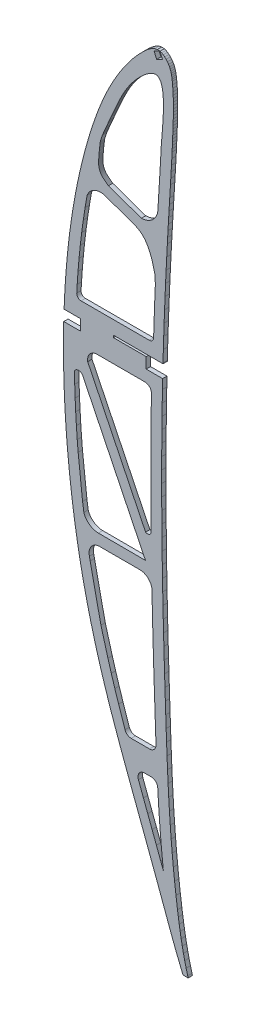
SolidWorks part; units mm, degrees
ref_plane "前视基准面" through (0, 0, 0) normal (0, 0, 1) x (1, 0, 0)
ref_plane "上视基准面" through (0, 0, 0) normal (0, 1, 0) x (1, 0, 0)
ref_plane "右视基准面" through (0, 0, 0) normal (1, 0, 0) x (0, 0, -1)
sketch "Model" plane through (0, 0, 0) normal (0, 0, 1) x (1, 0, 0)
  line L0 (80.8853, 6.7869) -> (80.6013, 7.44)
  line L1 (80.6013, 7.44) -> (79.4974, 10.0954)
  line L2 (79.4974, 10.0954) -> (78.4161, 12.7608)
  line L3 (78.4161, 12.7608) -> (77.3763, 15.3929)
  line L4 (77.3763, 15.3929) -> (76.3591, 18.0341)
  line L5 (76.3591, 18.0341) -> (75.3607, 20.682)
  line L6 (75.3607, 20.682) -> (74.3741, 23.3345)
  line L7 (74.3741, 23.3345) -> (73.3972, 25.9914)
  line L8 (73.3972, 25.9914) -> (71.4514, 31.3096)
  line L9 (71.4514, 31.3096) -> (69.4948, 36.6223)
  line L10 (69.4948, 36.6223) -> (67.5256, 41.9265)
  line L11 (67.5256, 41.9265) -> (65.5445, 47.2261)
  line L12 (65.5445, 47.2261) -> (63.5566, 52.5225)
  line L13 (63.5566, 52.5225) -> (61.5637, 57.8176)
  line L14 (61.5637, 57.8176) -> (59.5689, 63.1126)
  line L15 (59.5689, 63.1126) -> (57.5739, 68.4106)
  line L16 (57.5739, 68.4106) -> (55.595, 73.6833)
  line L17 (55.595, 73.6833) -> (53.6309, 78.9607)
  line L18 (53.6309, 78.9607) -> (51.6916, 84.2451)
  line L19 (51.6916, 84.2451) -> (49.7867, 89.5421)
  line L20 (49.7867, 89.5421) -> (47.9262, 94.854)
  line L21 (47.9262, 94.854) -> (46.1219, 100.1863)
  line L22 (46.1219, 100.1863) -> (44.3817, 105.5415)
  line L23 (44.3817, 105.5415) -> (42.7516, 110.8044)
  line L24 (42.7516, 110.8044) -> (41.1946, 116.0895)
  line L25 (41.1946, 116.0895) -> (39.7137, 121.395)
  line L26 (39.7137, 121.395) -> (38.308, 126.7217)
  line L27 (38.308, 126.7217) -> (36.9806, 132.0679)
  line L28 (36.9806, 132.0679) -> (35.7313, 137.4345)
  line L29 (35.7313, 137.4345) -> (34.5623, 142.8197)
  line L30 (34.5623, 142.8197) -> (33.4905, 148.133)
  line L31 (33.4905, 148.133) -> (32.4952, 153.4596)
  line L32 (32.4952, 153.4596) -> (31.5745, 158.7986)
  line L33 (31.5745, 158.7986) -> (30.7252, 164.1496)
  line L34 (30.7252, 164.1496) -> (29.9466, 169.5108)
  line L35 (29.9466, 169.5108) -> (29.2346, 174.8838)
  line L36 (29.2346, 174.8838) -> (28.5882, 180.2657)
  line L37 (28.5882, 180.2657) -> (28.0091, 185.6216)
  line L38 (28.0091, 185.6216) -> (27.4917, 190.9831)
  line L39 (27.4917, 190.9831) -> (27.0392, 196.3485)
  line L40 (27.0392, 196.3485) -> (26.6507, 201.7176)
  line L41 (26.6507, 201.7176) -> (26.3269, 207.0926)
  line L42 (26.3269, 207.0926) -> (26.069, 212.4715)
  line L43 (26.069, 212.4715) -> (25.8771, 217.8543)
  line L44 (25.8771, 217.8543) -> (25.7527, 223.247)
  line L45 (25.7527, 223.247) -> (25.6964, 228.6396)
  line L46 (25.6964, 228.6396) -> (25.7103, 234.0314)
  line L47 (25.7103, 234.0314) -> (25.8108, 240.4108)
  line L48 (25.979, 245.4108) -> (26.1854, 250.2005)
  line L49 (26.1854, 250.2005) -> (26.4937, 255.5881)
  line L50 (26.4937, 255.5881) -> (26.8835, 261.0353)
  line L51 (26.8835, 261.0353) -> (27.3567, 266.4741)
  line L52 (27.3567, 266.4741) -> (27.9154, 271.9036)
  line L53 (27.9154, 271.9036) -> (28.5647, 277.3221)
  line L54 (28.5647, 277.3221) -> (29.3075, 282.7286)
  line L55 (29.3075, 282.7286) -> (30.1482, 288.1194)
  line L56 (30.1482, 288.1194) -> (31.0916, 293.4957)
  line L57 (31.0916, 293.4957) -> (31.6136, 296.2351)
  line L58 (31.6136, 296.2351) -> (32.1639, 298.9677)
  line L59 (32.1639, 298.9677) -> (32.7416, 301.6935)
  line L60 (32.7416, 301.6935) -> (33.3475, 304.4135)
  line L61 (33.3475, 304.4135) -> (33.9827, 307.1278)
  line L62 (33.9827, 307.1278) -> (34.6473, 309.8343)
  line L63 (34.6473, 309.8343) -> (35.3421, 312.5352)
  line L64 (35.3421, 312.5352) -> (36.0863, 315.2993)
  line L65 (36.0863, 315.2993) -> (36.8648, 318.0549)
  line L66 (36.8648, 318.0549) -> (37.6779, 320.799)
  line L67 (37.6779, 320.799) -> (38.5296, 323.5307)
  line L68 (38.5296, 323.5307) -> (39.4217, 326.2512)
  line L69 (39.4217, 326.2512) -> (40.3556, 328.9575)
  line L70 (40.3556, 328.9575) -> (41.3351, 331.6498)
  line L71 (41.3351, 331.6498) -> (41.8619, 333.0401)
  line L72 (41.8619, 333.0401) -> (42.401, 334.426)
  line L73 (42.401, 334.426) -> (42.9544, 335.8054)
  line L74 (42.9544, 335.8054) -> (43.522, 337.1785)
  line L75 (43.522, 337.1785) -> (44.105, 338.5432)
  line L76 (44.105, 338.5432) -> (44.7043, 339.9016)
  line L77 (44.7043, 339.9016) -> (45.3191, 341.2507)
  line L78 (45.3191, 341.2507) -> (45.9834, 342.6561)
  line L79 (45.9834, 342.6561) -> (46.6672, 344.0522)
  line L80 (46.6672, 344.0522) -> (47.3714, 345.4383)
  line L81 (47.3714, 345.4383) -> (48.097, 346.8152)
  line L82 (48.097, 346.8152) -> (48.843, 348.1841)
  line L83 (48.843, 348.1841) -> (49.6134, 349.545)
  line L84 (49.6134, 349.545) -> (50.4061, 350.8988)
  line L85 (50.4061, 350.8988) -> (51.2905, 352.3538)
  line L86 (51.2905, 352.3538) -> (52.2005, 353.7948)
  line L87 (52.2005, 353.7948) -> (53.1343, 355.2179)
  line L88 (53.1343, 355.2179) -> (54.0902, 356.616)
  line L89 (54.0902, 356.616) -> (55.0674, 357.9859)
  line L90 (55.0674, 357.9859) -> (56.0621, 359.3215)
  line L91 (56.0621, 359.3215) -> (57.0745, 360.6169)
  line L92 (57.0745, 360.6169) -> (57.7043, 361.3932)
  line L93 (57.7043, 361.3932) -> (58.3456, 362.1569)
  line L94 (58.3456, 362.1569) -> (59.0031, 362.9163)
  line L95 (59.0031, 362.9163) -> (59.6826, 363.6756)
  line L96 (59.6826, 363.6756) -> (60.3889, 364.4412)
  line L97 (60.3889, 364.4412) -> (61.1287, 365.2182)
  line L98 (61.1287, 365.2182) -> (61.9058, 366.0128)
  line L99 (61.9058, 366.0128) -> (62.9912, 367.0802)
  line L100 (62.9912, 367.0802) -> (64.1359, 368.1221)
  line L101 (64.1359, 368.1221) -> (65.3256, 369.0719)
  line L102 (65.3256, 369.0719) -> (66.5452, 369.8629)
  line L103 (66.5452, 369.8629) -> (67.7798, 370.4282)
  line L104 (67.7798, 370.4282) -> (69.015, 370.7024)
  line L105 (69.015, 370.7024) -> (70.2338, 370.6185)
  line L106 (70.2338, 370.6185) -> (70.9807, 370.3608)
  line L107 (70.9807, 370.3608) -> (71.705, 369.959)
  line L108 (71.705, 369.959) -> (72.3954, 369.4366)
  line L109 (72.3954, 369.4366) -> (73.0402, 368.8132)
  line L110 (73.0402, 368.8132) -> (73.6293, 368.1132)
  line L111 (73.6293, 368.1132) -> (74.1518, 367.3563)
  line L112 (74.1518, 367.3563) -> (74.5967, 366.5669)
  line L113 (74.5967, 366.5669) -> (74.9201, 365.8533)
  line L114 (74.9201, 365.8533) -> (75.1829, 365.1311)
  line L115 (75.1829, 365.1311) -> (75.3928, 364.4026)
  line L116 (75.3928, 364.4026) -> (75.559, 363.6681)
  line L117 (75.559, 363.6681) -> (75.6914, 362.9282)
  line L118 (75.6914, 362.9282) -> (75.7979, 362.1851)
  line L119 (75.7979, 362.1851) -> (75.8876, 361.4383)
  line L120 (75.8876, 361.4383) -> (76.0269, 360.1051)
  line L121 (76.0269, 360.1051) -> (76.1424, 358.7659)
  line L122 (76.1424, 358.7659) -> (76.2351, 357.4237)
  line L123 (76.2351, 357.4237) -> (76.3068, 356.0785)
  line L124 (76.3068, 356.0785) -> (76.3596, 354.7315)
  line L125 (76.3596, 354.7315) -> (76.3945, 353.3828)
  line L126 (76.3945, 353.3828) -> (76.4123, 352.0343)
  line L127 (76.4123, 352.0343) -> (76.4142, 350.6851)
  line L128 (76.4142, 350.6851) -> (76.403, 349.3353)
  line L129 (76.403, 349.3353) -> (76.3798, 347.988)
  line L130 (76.3798, 347.988) -> (76.3465, 346.6403)
  line L131 (76.3465, 346.6403) -> (76.3062, 345.2932)
  line L132 (76.3062, 345.2932) -> (76.2599, 343.9469)
  line L133 (76.2599, 343.9469) -> (76.2107, 342.5995)
  line L134 (76.2107, 342.5995) -> (76.1585, 341.2499)
  line L135 (76.1585, 341.2499) -> (76.1053, 339.9003)
  line L136 (76.1053, 339.9003) -> (76.0491, 338.5516)
  line L137 (76.0491, 338.5516) -> (75.9918, 337.2028)
  line L138 (75.9918, 337.2028) -> (75.9317, 335.8529)
  line L139 (75.9317, 335.8529) -> (75.8695, 334.5039)
  line L140 (75.8695, 334.5039) -> (75.8052, 333.1548)
  line L141 (75.8052, 333.1548) -> (75.668, 330.4533)
  line L142 (75.668, 330.4533) -> (75.5216, 327.7523)
  line L143 (75.5216, 327.7523) -> (75.3683, 325.0521)
  line L144 (75.3683, 325.0521) -> (75.2089, 322.3525)
  line L145 (75.2089, 322.3525) -> (75.0464, 319.6539)
  line L146 (75.0464, 319.6539) -> (74.7156, 314.2543)
  line L147 (74.7156, 314.2543) -> (74.5523, 311.5536)
  line L148 (74.5523, 311.5536) -> (74.3899, 308.853)
  line L149 (74.3899, 308.853) -> (74.2295, 306.1534)
  line L150 (74.2295, 306.1534) -> (74.0721, 303.454)
  line L151 (74.0721, 303.454) -> (73.9167, 300.7546)
  line L152 (73.9167, 300.7546) -> (73.7644, 298.0534)
  line L153 (73.7644, 298.0534) -> (73.6161, 295.3524)
  line L154 (73.6161, 295.3524) -> (73.3292, 289.9557)
  line L155 (73.3292, 289.9557) -> (73.0573, 284.5597)
  line L156 (73.0573, 284.5597) -> (72.8014, 279.1644)
  line L157 (72.8014, 279.1644) -> (72.5605, 273.7688)
  line L158 (72.5605, 273.7688) -> (72.3357, 268.3718)
  line L159 (72.3357, 268.3718) -> (72.128, 262.9726)
  line L160 (72.128, 262.9726) -> (71.9384, 257.5722)
  line L161 (71.9384, 257.5722) -> (71.7655, 252.1795)
  line L162 (71.7655, 252.1795) -> (71.6105, 246.7887)
  line L163 (71.6105, 246.7887) -> (71.6009, 246.4108)
  line L164 (71.4292, 240.4108) -> (71.3535, 236.0072)
  line L165 (71.3535, 236.0072) -> (71.2516, 230.6156)
  line L166 (71.2516, 230.6156) -> (71.1668, 225.2228)
  line L167 (71.1668, 225.2228) -> (71.1, 219.8287)
  line L168 (71.1, 219.8287) -> (71.05, 214.4404)
  line L169 (71.05, 214.4404) -> (71.0169, 209.0538)
  line L170 (71.0169, 209.0538) -> (70.9998, 203.668)
  line L171 (70.9998, 203.668) -> (70.9987, 198.2818)
  line L172 (70.9987, 198.2818) -> (71.0127, 192.8963)
  line L173 (71.0127, 192.8963) -> (71.0407, 187.5094)
  line L174 (71.0407, 187.5094) -> (71.0817, 182.121)
  line L175 (71.0817, 182.121) -> (71.1367, 176.7363)
  line L176 (71.1367, 176.7363) -> (71.2046, 171.3532)
  line L177 (71.2046, 171.3532) -> (71.2844, 165.9705)
  line L178 (71.2844, 165.9705) -> (71.3772, 160.5894)
  line L179 (71.3772, 160.5894) -> (71.4821, 155.2079)
  line L180 (71.4821, 155.2079) -> (71.5979, 149.8258)
  line L181 (71.5979, 149.8258) -> (71.7269, 144.4423)
  line L182 (71.7269, 144.4423) -> (71.8658, 139.0603)
  line L183 (71.8658, 139.0603) -> (72.0156, 133.6807)
  line L184 (72.0156, 133.6807) -> (72.1743, 128.3025)
  line L185 (72.1743, 128.3025) -> (72.3411, 122.9246)
  line L186 (72.3411, 122.9246) -> (72.5138, 117.546)
  line L187 (72.5138, 117.546) -> (72.6926, 112.1667)
  line L188 (72.6926, 112.1667) -> (72.8755, 106.7856)
  line L189 (72.8755, 106.7856) -> (73.0624, 101.4046)
  line L190 (73.0624, 101.4046) -> (73.2582, 96.026)
  line L191 (73.2582, 96.026) -> (73.468, 90.6491)
  line L192 (73.468, 90.6491) -> (73.6997, 85.2731)
  line L193 (73.6997, 85.2731) -> (73.9573, 79.8992)
  line L194 (73.9573, 79.8992) -> (74.248, 74.5257)
  line L195 (74.248, 74.5257) -> (74.5777, 69.153)
  line L196 (74.5777, 69.153) -> (74.9516, 63.7752)
  line L197 (74.9516, 63.7752) -> (75.3734, 58.4025)
  line L198 (75.3734, 58.4025) -> (75.845, 53.0339)
  line L199 (75.845, 53.0339) -> (76.3714, 47.6708)
  line L200 (76.3714, 47.6708) -> (76.9547, 42.3122)
  line L201 (76.9547, 42.3122) -> (77.5979, 36.9581)
  line L202 (77.5979, 36.9581) -> (78.3039, 31.6088)
  line L203 (78.3039, 31.6088) -> (78.6857, 28.9169)
  line L204 (78.6857, 28.9169) -> (79.0902, 26.23)
  line L205 (79.0902, 26.23) -> (79.5207, 23.5472)
  line L206 (79.5207, 23.5472) -> (79.9848, 20.8729)
  line L207 (79.9848, 20.8729) -> (80.4876, 18.2053)
  line L208 (80.4876, 18.2053) -> (81.034, 15.5476)
  line L209 (81.034, 15.5476) -> (81.6301, 12.9011)
  line L210 (81.6301, 12.9011) -> (82.2909, 10.2144)
  line L211 (82.2909, 10.2144) -> (83.0012, 7.5408)
  line L212 (83.0012, 7.5408) -> (83.2283, 6.7869)
  line L213 (83.2283, 6.7869) -> (80.8853, 6.7869)
  line L214 (70.8079, 333.1553) -> (70.668, 330.4533)
  line L215 (70.668, 330.4533) -> (70.5216, 327.7523)
  line L216 (70.5216, 327.7523) -> (70.3683, 325.0521)
  line L217 (70.3683, 325.0521) -> (70.2089, 322.3525)
  line L218 (70.2089, 322.3525) -> (70.0464, 319.6539)
  line L219 (70.0464, 319.6539) -> (69.7156, 314.2543)
  line L220 (69.7156, 314.2543) -> (69.5523, 311.5536)
  line L221 (69.5523, 311.5536) -> (69.3899, 308.853)
  line L222 (69.3899, 308.853) -> (69.2295, 306.1534)
  line L223 (67.8279, 280.4453) -> (68.0825, 276.5082)
  line L224 (68.0825, 276.5082) -> (67.8577, 271.1112)
  line L225 (67.8577, 271.1112) -> (67.6501, 265.712)
  line L226 (67.6501, 265.712) -> (67.4604, 260.3116)
  line L227 (67.4604, 260.3116) -> (67.2875, 254.9189)
  line L228 (67.2875, 254.9189) -> (67.2781, 254.5927)
  line L229 (65.2789, 252.6501) -> (33.8086, 252.6501)
  line L230 (31.8118, 254.7644) -> (32.0157, 258.3274)
  line L231 (32.0157, 258.3274) -> (32.4055, 263.7746)
  line L232 (32.4055, 263.7746) -> (32.8787, 269.2134)
  line L233 (32.8787, 269.2134) -> (33.4374, 274.643)
  line L234 (33.4374, 274.643) -> (34.0867, 280.0615)
  line L235 (34.0867, 280.0615) -> (34.8296, 285.468)
  line L236 (34.8296, 285.468) -> (35.6702, 290.8588)
  line L237 (35.6702, 290.8588) -> (36.6136, 296.2351)
  line L238 (25.979, 245.4108) -> (32.5375, 245.4108)
  line L239 (46.4379, 304.9504) -> (61.6579, 299.5863)
  line L240 (45.1073, 300.1185) -> (55.8979, 296.3173)
  line L241 (48.7755, 245.4108) -> (48.7755, 246.4108)
  line L242 (48.7755, 246.4108) -> (71.6009, 246.4108)
  line L243 (48.7755, 245.4108) -> (63.8719, 245.4108)
  line L244 (70.1941, 370.5895) -> (67.4692, 369.3364)
  line L245 (67.4692, 369.3364) -> (68.7212, 366.6114)
  line L246 (68.7212, 366.6114) -> (71.4472, 367.8635)
  line L247 (71.4472, 367.8635) -> (70.1941, 370.5895)
  line L248 (63.8719, 240.4108) -> (63.8719, 245.4108)
  line L249 (33.5375, 240.4108) -> (33.5375, 245.4108)
  line L250 (33.5375, 245.4108) -> (32.5375, 245.4108)
  line L251 (69.1796, 75.7899) -> (69.248, 74.5257)
  line L252 (69.248, 74.5257) -> (69.5777, 69.153)
  line L253 (69.5777, 69.153) -> (69.9516, 63.7752)
  line L254 (69.9516, 63.7752) -> (70.3734, 58.4025)
  line L255 (70.3734, 58.4025) -> (70.845, 53.0339)
  line L256 (70.845, 53.0339) -> (71.7794, 43.9225)
  line L257 (71.7794, 43.9225) -> (70.5445, 47.2261)
  line L258 (70.5445, 47.2261) -> (68.5566, 52.5225)
  line L259 (68.5566, 52.5225) -> (66.5637, 57.8176)
  line L260 (66.5637, 57.8176) -> (64.5689, 63.1126)
  line L261 (64.5689, 63.1126) -> (62.5739, 68.4106)
  line L262 (62.5739, 68.4106) -> (60.2608, 74.5737)
  line L263 (63.0695, 78.6278) -> (66.184, 78.6278)
  line L264 (34.5052, 172.8415) -> (35.096, 168.7702)
  line L265 (66.1092, 179.4287) -> (66.1402, 176.5617)
  line L266 (41.8041, 163.8587) -> (63.5371, 163.7929)
  line L267 (66.4821, 154.2874) -> (66.5979, 149.8258)
  line L268 (66.5979, 149.8258) -> (66.7269, 144.4423)
  line L269 (66.7269, 144.4423) -> (66.8658, 139.0603)
  line L270 (66.8658, 139.0603) -> (67.0156, 133.6807)
  line L271 (67.0156, 133.6807) -> (67.3276, 123.1102)
  line L272 (32.4506, 191.4706) -> (32.0392, 196.3485)
  line L273 (32.0392, 196.3485) -> (31.6507, 201.7176)
  line L274 (31.6507, 201.7176) -> (31.3269, 207.0926)
  line L275 (31.3269, 207.0926) -> (31.069, 212.4715)
  line L276 (31.069, 212.4715) -> (30.8771, 217.8543)
  line L277 (30.8771, 217.8543) -> (30.7527, 223.247)
  line L278 (41.1836, 234.9868) -> (63.2728, 234.9868)
  line L279 (66.2724, 231.9396) -> (66.1668, 225.2228)
  line L280 (66.1668, 225.2228) -> (66.1, 219.8287)
  line L281 (65.9993, 201.1058) -> (65.9987, 198.2818)
  line L282 (65.9987, 198.2818) -> (66.0127, 192.8963)
  line L283 (66.0127, 192.8963) -> (66.0407, 187.5094)
  line L284 (66.0407, 187.5094) -> (66.0817, 182.121)
  line L285 (66.0817, 182.121) -> (66.1092, 179.4287)
  line L286 (37.9929, 150.7963) -> (37.654, 152.5392)
  line L287 (68.2243, 96.9576) -> (68.3862, 92.5107)
  line L288 (65.3882, 89.4015) -> (56.9232, 89.4015)
  line L289 (54.0814, 91.44) -> (51.1219, 100.1863)
  line L290 (51.1219, 100.1863) -> (49.3817, 105.5415)
  line L291 (49.3817, 105.5415) -> (47.7516, 110.8044)
  line L292 (47.7516, 110.8044) -> (46.1946, 116.0895)
  line L293 (46.1946, 116.0895) -> (42.9636, 127.6653)
  line L294 (33.5375, 240.4108) -> (25.8108, 240.4108)
  line L295 (63.8719, 240.4108) -> (71.4292, 240.4108)
  line L296 (32.4506, 191.4706) -> (34.5052, 172.8415)
  line L297 (42.9636, 127.6653) -> (37.9929, 150.7963)
  line L298 (68.2243, 96.9576) -> (67.3276, 123.1102)
  line L299 (65.9993, 201.1058) -> (66.1, 219.8287)
  line L300 (63.5763, 175.1182) -> (36.8687, 229.8768)
  line L301 (63.5371, 163.7929) -> (34.6638, 222.9921)
  line L302 (61.2175, 158.7878) -> (43.0281, 158.7878)
  line L303 (42.6779, 320.7993) -> (43.6579, 323.8303)
  line L304 (43.6579, 323.8303) -> (43.7879, 324.1303)
  line L305 (43.7879, 324.1303) -> (43.9179, 324.4303)
  line L306 (43.9179, 324.4303) -> (44.0379, 324.7293)
  line L307 (44.0379, 324.7293) -> (44.1679, 325.0293)
  line L308 (44.1679, 325.0293) -> (44.2979, 325.3293)
  line L309 (44.2979, 325.3293) -> (44.4279, 325.6283)
  line L310 (44.4279, 325.6283) -> (44.5579, 325.9283)
  line L311 (44.5579, 325.9283) -> (44.6879, 326.2273)
  line L312 (44.6879, 326.2273) -> (44.8079, 326.5263)
  line L313 (44.8079, 326.5263) -> (44.9379, 326.8263)
  line L314 (44.9379, 326.8263) -> (45.0679, 327.1253)
  line L315 (45.0679, 327.1253) -> (45.1979, 327.4243)
  line L316 (45.1979, 327.4243) -> (45.3279, 327.7223)
  line L317 (45.3279, 327.7223) -> (45.4579, 328.0213)
  line L318 (45.4579, 328.0213) -> (45.5779, 328.3203)
  line L319 (45.5779, 328.3203) -> (45.7079, 328.6183)
  line L320 (45.7079, 328.6183) -> (45.8379, 328.9163)
  line L321 (45.8379, 328.9163) -> (45.9679, 329.2143)
  line L322 (45.9679, 329.2143) -> (46.0979, 329.5123)
  line L323 (46.0979, 329.5123) -> (46.2279, 329.8093)
  line L324 (46.2279, 329.8093) -> (46.3479, 330.1063)
  line L325 (46.3479, 330.1063) -> (46.4779, 330.4043)
  line L326 (46.4779, 330.4043) -> (46.6079, 330.7003)
  line L327 (46.6079, 330.7003) -> (46.7379, 330.9973)
  line L328 (46.7379, 330.9973) -> (46.8679, 331.2933)
  line L329 (46.8679, 331.2933) -> (46.9879, 331.5893)
  line L330 (46.9879, 331.5893) -> (47.1179, 331.8853)
  line L331 (47.1179, 331.8853) -> (47.2479, 332.1803)
  line L332 (47.2479, 332.1803) -> (47.3779, 332.4753)
  line L333 (47.3779, 332.4753) -> (47.5079, 332.7703)
  line L334 (47.5079, 332.7703) -> (47.6379, 333.0653)
  line L335 (47.6379, 333.0653) -> (47.7679, 333.3593)
  line L336 (47.7679, 333.3593) -> (47.8879, 333.6533)
  line L337 (47.8879, 333.6533) -> (48.0179, 333.9463)
  line L338 (48.0179, 333.9463) -> (48.1479, 334.2393)
  line L339 (48.1479, 334.2393) -> (48.2779, 334.5323)
  line L340 (48.2779, 334.5323) -> (48.4079, 334.8243)
  line L341 (48.4079, 334.8243) -> (48.5379, 335.1163)
  line L342 (48.5379, 335.1163) -> (48.6579, 335.4073)
  line L343 (48.6579, 335.4073) -> (48.7879, 335.6983)
  line L344 (48.7879, 335.6983) -> (48.9179, 335.9893)
  line L345 (48.9179, 335.9893) -> (49.0479, 336.2793)
  line L346 (49.0479, 336.2793) -> (49.1779, 336.5693)
  line L347 (49.1779, 336.5693) -> (49.3079, 336.8583)
  line L348 (49.3079, 336.8583) -> (49.4379, 337.1463)
  line L349 (49.4379, 337.1463) -> (49.5579, 337.4353)
  line L350 (49.5579, 337.4353) -> (49.6879, 337.7223)
  line L351 (49.6879, 337.7223) -> (49.8179, 338.0093)
  line L352 (49.8179, 338.0093) -> (49.9479, 338.2963)
  line L353 (49.9479, 338.2963) -> (50.0779, 338.5823)
  line L354 (50.0779, 338.5823) -> (50.2079, 338.8683)
  line L355 (50.2079, 338.8683) -> (50.3379, 339.1533)
  line L356 (50.3379, 339.1533) -> (50.4579, 339.4373)
  line L357 (50.4579, 339.4373) -> (50.5879, 339.7213)
  line L358 (50.5879, 339.7213) -> (50.7179, 340.0053)
  line L359 (50.7179, 340.0053) -> (50.8479, 340.2883)
  line L360 (50.8479, 340.2883) -> (50.9779, 340.5703)
  line L361 (50.9779, 340.5703) -> (51.1079, 340.8523)
  line L362 (51.1079, 340.8523) -> (51.2379, 341.1343)
  line L363 (51.2379, 341.1343) -> (51.3779, 341.4153)
  line L364 (51.3779, 341.4153) -> (51.5079, 341.6963)
  line L365 (51.5079, 341.6963) -> (51.6379, 341.9763)
  line L366 (51.6379, 341.9763) -> (51.7779, 342.2553)
  line L367 (51.7779, 342.2553) -> (51.9079, 342.5353)
  line L368 (51.9079, 342.5353) -> (52.0479, 342.8143)
  line L369 (52.0479, 342.8143) -> (52.1779, 343.0923)
  line L370 (52.1779, 343.0923) -> (52.3179, 343.3703)
  line L371 (52.3179, 343.3703) -> (52.4579, 343.6483)
  line L372 (52.4579, 343.6483) -> (52.5979, 343.9253)
  line L373 (52.5979, 343.9253) -> (52.7479, 344.2023)
  line L374 (52.7479, 344.2023) -> (52.8879, 344.4793)
  line L375 (52.8879, 344.4793) -> (53.0379, 344.7553)
  line L376 (53.0379, 344.7553) -> (53.1779, 345.0313)
  line L377 (53.1779, 345.0313) -> (53.3279, 345.3073)
  line L378 (53.3279, 345.3073) -> (53.4779, 345.5823)
  line L379 (53.4779, 345.5823) -> (53.6279, 345.8573)
  line L380 (53.6279, 345.8573) -> (53.7879, 346.1323)
  line L381 (53.7879, 346.1323) -> (53.9379, 346.4063)
  line L382 (53.9379, 346.4063) -> (54.0979, 346.6803)
  line L383 (54.0979, 346.6803) -> (54.2579, 346.9543)
  line L384 (54.2579, 346.9543) -> (54.4179, 347.2283)
  line L385 (54.4179, 347.2283) -> (54.5879, 347.5013)
  line L386 (54.5879, 347.5013) -> (54.7579, 347.7743)
  line L387 (54.7579, 347.7743) -> (54.9279, 348.0473)
  line L388 (54.9279, 348.0473) -> (55.0979, 348.3203)
  line L389 (55.0979, 348.3203) -> (55.2679, 348.5923)
  line L390 (55.2679, 348.5923) -> (55.4479, 348.8653)
  line L391 (55.4479, 348.8653) -> (55.6279, 349.1373)
  line L392 (55.6279, 349.1373) -> (55.8079, 349.4093)
  line L393 (55.8079, 349.4093) -> (55.9979, 349.6803)
  line L394 (55.9979, 349.6803) -> (56.1779, 349.9523)
  line L395 (56.1779, 349.9523) -> (56.3779, 350.2233)
  line L396 (56.3779, 350.2233) -> (56.5679, 350.4953)
  line L397 (56.5679, 350.4953) -> (56.7679, 350.7663)
  line L398 (56.7679, 350.7663) -> (56.9679, 351.0373)
  line L399 (56.9679, 351.0373) -> (57.1679, 351.3083)
  line L400 (57.1679, 351.3083) -> (57.3779, 351.5793)
  line L401 (57.3779, 351.5793) -> (57.5879, 351.8503)
  line L402 (57.5879, 351.8503) -> (57.8079, 352.1203)
  line L403 (57.8079, 352.1203) -> (58.0179, 352.3913)
  line L404 (58.0179, 352.3913) -> (58.2379, 352.6613)
  line L405 (58.2379, 352.6613) -> (58.4679, 352.9323)
  line L406 (58.4679, 352.9323) -> (58.6979, 353.2023)
  line L407 (58.6979, 353.2023) -> (58.9279, 353.4733)
  line L408 (58.9279, 353.4733) -> (59.1679, 353.7433)
  line L409 (59.1679, 353.7433) -> (59.4079, 354.0143)
  line L410 (59.4079, 354.0143) -> (59.6479, 354.2843)
  line L411 (59.6479, 354.2843) -> (59.8979, 354.5533)
  line L412 (59.8979, 354.5533) -> (60.1479, 354.8223)
  line L413 (60.1479, 354.8223) -> (60.4079, 355.0893)
  line L414 (60.4079, 355.0893) -> (60.6679, 355.3543)
  line L415 (60.6679, 355.3543) -> (60.9279, 355.6173)
  line L416 (60.9279, 355.6173) -> (61.1879, 355.8773)
  line L417 (61.1879, 355.8773) -> (61.4479, 356.1343)
  line L418 (61.4479, 356.1343) -> (61.7179, 356.3873)
  line L419 (61.7179, 356.3873) -> (61.9779, 356.6373)
  line L420 (61.9779, 356.6373) -> (62.2479, 356.8823)
  line L421 (62.2479, 356.8823) -> (62.5079, 357.1223)
  line L422 (62.5079, 357.1223) -> (62.7779, 357.3563)
  line L423 (62.7779, 357.3563) -> (63.0479, 357.5853)
  line L424 (63.0479, 357.5853) -> (63.3079, 357.8083)
  line L425 (63.3079, 357.8083) -> (63.5779, 358.0253)
  line L426 (63.5779, 358.0253) -> (63.8379, 358.2343)
  line L427 (63.8379, 358.2343) -> (64.1079, 358.4373)
  line L428 (64.1079, 358.4373) -> (64.3679, 358.6313)
  line L429 (64.3679, 358.6313) -> (64.6279, 358.8173)
  line L430 (64.6279, 358.8173) -> (64.8779, 358.9943)
  line L431 (64.8779, 358.9943) -> (65.1379, 359.1633)
  line L432 (65.1379, 359.1633) -> (65.3879, 359.3223)
  line L433 (65.3879, 359.3223) -> (65.6279, 359.4713)
  line L434 (65.6279, 359.4713) -> (65.8779, 359.6103)
  line L435 (65.8779, 359.6103) -> (66.1179, 359.7373)
  line L436 (66.1179, 359.7373) -> (66.3479, 359.8543)
  line L437 (66.3479, 359.8543) -> (66.5779, 359.9593)
  line L438 (66.5779, 359.9593) -> (66.8079, 360.0533)
  line L439 (66.8079, 360.0533) -> (67.0279, 360.1333)
  line L440 (67.0279, 360.1333) -> (67.2379, 360.2013)
  line L441 (67.2379, 360.2013) -> (67.4479, 360.2563)
  line L442 (67.4479, 360.2563) -> (67.6479, 360.2973)
  line L443 (67.6479, 360.2973) -> (67.8479, 360.3263)
  line L444 (67.8479, 360.3263) -> (68.0379, 360.3413)
  line L445 (68.0379, 360.3413) -> (68.2279, 360.3443)
  line L446 (68.2279, 360.3443) -> (68.4079, 360.3343)
  line L447 (68.4079, 360.3343) -> (68.5779, 360.3113)
  line L448 (68.5779, 360.3113) -> (68.7479, 360.2773)
  line L449 (68.7479, 360.2773) -> (68.9079, 360.2303)
  line L450 (68.9079, 360.2303) -> (69.0679, 360.1713)
  line L451 (69.0679, 360.1713) -> (69.2279, 360.1003)
  line L452 (69.2279, 360.1003) -> (69.3679, 360.0183)
  line L453 (69.3679, 360.0183) -> (69.5179, 359.9243)
  line L454 (69.5179, 359.9243) -> (69.6479, 359.8193)
  line L455 (69.6479, 359.8193) -> (69.7779, 359.7033)
  line L456 (69.7779, 359.7033) -> (69.9079, 359.5753)
  line L457 (69.9079, 359.5753) -> (70.0279, 359.4373)
  line L458 (70.0279, 359.4373) -> (70.1479, 359.2883)
  line L459 (70.1479, 359.2883) -> (70.2579, 359.1293)
  line L460 (70.2579, 359.1293) -> (70.3679, 358.9593)
  line L461 (70.3679, 358.9593) -> (70.4779, 358.7793)
  line L462 (70.4779, 358.7793) -> (70.5779, 358.5883)
  line L463 (70.5779, 358.5883) -> (70.6679, 358.3883)
  line L464 (70.6679, 358.3883) -> (70.7579, 358.1783)
  line L465 (70.7579, 358.1783) -> (70.8479, 357.9593)
  line L466 (70.8479, 357.9593) -> (70.9279, 357.7303)
  line L467 (70.9279, 357.7303) -> (71.0079, 357.4913)
  line L468 (71.0079, 357.4913) -> (71.0779, 357.2443)
  line L469 (71.0779, 357.2443) -> (71.1479, 356.9883)
  line L470 (71.1479, 356.9883) -> (71.2179, 356.7223)
  line L471 (71.2179, 356.7223) -> (71.2779, 356.4483)
  line L472 (71.2779, 356.4483) -> (71.3379, 356.1663)
  line L473 (71.3379, 356.1663) -> (71.3879, 355.8753)
  line L474 (71.3879, 355.8753) -> (71.4379, 355.5763)
  line L475 (71.4379, 355.5763) -> (71.4879, 355.2693)
  line L476 (71.4879, 355.2693) -> (71.5279, 354.9543)
  line L477 (71.5279, 354.9543) -> (71.5679, 354.6323)
  line L478 (71.5679, 354.6323) -> (71.6079, 354.3023)
  line L479 (71.6079, 354.3023) -> (71.6379, 353.9643)
  line L480 (71.6379, 353.9643) -> (71.6679, 353.6193)
  line L481 (71.6679, 353.6193) -> (71.6979, 353.2673)
  line L482 (71.6979, 353.2673) -> (71.7179, 352.9083)
  line L483 (71.7179, 352.9083) -> (71.7379, 352.5433)
  line L484 (71.7379, 352.5433) -> (71.7579, 352.1713)
  line L485 (71.7579, 352.1713) -> (71.7679, 351.7923)
  line L486 (71.7679, 351.7923) -> (71.7879, 351.4073)
  line L487 (71.7879, 351.4073) -> (71.7979, 351.0163)
  line L488 (71.7979, 351.0163) -> (71.7979, 350.6193)
  line L489 (71.7979, 350.6193) -> (71.8079, 350.2163)
  line L490 (71.8079, 350.2163) -> (71.8079, 349.8073)
  line L491 (71.8079, 349.8073) -> (71.8079, 349.3933)
  line L492 (71.8079, 349.3933) -> (71.7979, 348.9733)
  line L493 (71.7979, 348.9733) -> (71.7979, 348.5483)
  line L494 (71.7979, 348.5483) -> (71.7879, 348.1193)
  line L495 (71.7879, 348.1193) -> (71.7779, 347.6843)
  line L496 (71.7779, 347.6843) -> (71.7679, 347.2453)
  line L497 (71.7679, 347.2453) -> (71.7479, 346.8013)
  line L498 (71.7479, 346.8013) -> (71.7379, 346.3523)
  line L499 (71.7379, 346.3523) -> (71.7179, 345.9003)
  line L500 (71.7179, 345.9003) -> (71.6979, 345.4433)
  line L501 (71.6979, 345.4433) -> (71.6779, 344.9823)
  line L502 (71.6779, 344.9823) -> (71.6479, 344.5183)
  line L503 (71.6479, 344.5183) -> (71.6279, 344.0503)
  line L504 (71.6279, 344.0503) -> (71.5979, 343.5783)
  line L505 (71.5979, 343.5783) -> (71.5679, 343.1043)
  line L506 (71.5679, 343.1043) -> (71.5379, 342.6263)
  line L507 (71.5379, 342.6263) -> (71.5079, 342.1453)
  line L508 (71.5079, 342.1453) -> (71.4779, 341.6613)
  line L509 (71.4779, 341.6613) -> (71.4479, 341.1743)
  line L510 (71.4479, 341.1743) -> (71.4079, 340.6853)
  line L511 (71.4079, 340.6853) -> (71.3779, 340.1943)
  line L512 (71.3779, 340.1943) -> (71.3379, 339.7003)
  line L513 (71.3379, 339.7003) -> (71.2979, 339.2053)
  line L514 (71.2979, 339.2053) -> (71.2579, 338.7073)
  line L515 (71.2579, 338.7073) -> (71.2279, 338.2083)
  line L516 (71.2279, 338.2083) -> (71.1879, 337.7073)
  line L517 (71.1879, 337.7073) -> (71.1479, 337.2053)
  line L518 (71.1479, 337.2053) -> (71.0979, 336.7013)
  line L519 (71.0979, 336.7013) -> (71.0579, 336.1973)
  line L520 (71.0579, 336.1973) -> (71.0179, 335.6913)
  line L521 (71.0179, 335.6913) -> (70.9779, 335.1853)
  line L522 (70.9779, 335.1853) -> (70.9379, 334.6783)
  line L523 (70.9379, 334.6783) -> (70.8879, 334.1703)
  line L524 (70.8879, 334.1703) -> (70.8479, 333.6623)
  line L525 (70.8479, 333.6623) -> (70.8079, 333.1553)
  line L526 (42.6779, 320.7993) -> (42.6679, 320.7093)
  line L527 (42.6679, 320.7093) -> (42.6579, 320.6193)
  line L528 (42.6579, 320.6193) -> (42.6479, 320.5303)
  line L529 (42.6479, 320.5303) -> (42.6379, 320.4403)
  line L530 (42.6379, 320.4403) -> (42.6279, 320.3503)
  line L531 (42.6279, 320.3503) -> (42.6079, 320.2613)
  line L532 (42.6079, 320.2613) -> (42.5979, 320.1713)
  line L533 (42.5979, 320.1713) -> (42.5879, 320.0813)
  line L534 (42.5879, 320.0813) -> (42.5779, 319.9923)
  line L535 (42.5779, 319.9923) -> (42.5679, 319.9023)
  line L536 (42.5679, 319.9023) -> (42.5579, 319.8123)
  line L537 (42.5579, 319.8123) -> (42.5479, 319.7223)
  line L538 (42.5479, 319.7223) -> (42.5379, 319.6333)
  line L539 (42.5379, 319.6333) -> (42.5279, 319.5433)
  line L540 (42.5279, 319.5433) -> (42.5179, 319.4533)
  line L541 (42.5179, 319.4533) -> (42.5079, 319.3633)
  line L542 (42.5079, 319.3633) -> (42.4979, 319.2733)
  line L543 (42.4979, 319.2733) -> (42.4779, 319.1833)
  line L544 (42.4779, 319.1833) -> (42.4679, 319.0933)
  line L545 (42.4679, 319.0933) -> (42.4579, 319.0033)
  line L546 (42.4579, 319.0033) -> (42.4479, 318.9133)
  line L547 (42.4479, 318.9133) -> (42.4379, 318.8233)
  line L548 (42.4379, 318.8233) -> (42.4279, 318.7333)
  line L549 (42.4279, 318.7333) -> (42.4179, 318.6433)
  line L550 (42.4179, 318.6433) -> (42.4079, 318.5533)
  line L551 (42.4079, 318.5533) -> (42.3979, 318.4623)
  line L552 (42.3979, 318.4623) -> (42.3879, 318.3723)
  line L553 (42.3879, 318.3723) -> (42.3779, 318.2823)
  line L554 (42.3779, 318.2823) -> (42.3679, 318.1913)
  line L555 (42.3679, 318.1913) -> (42.3579, 318.1013)
  line L556 (42.3579, 318.1013) -> (42.3479, 318.0103)
  line L557 (42.3479, 318.0103) -> (42.3379, 317.9203)
  line L558 (42.3379, 317.9203) -> (42.3279, 317.8293)
  line L559 (42.3279, 317.8293) -> (42.3179, 317.7383)
  line L560 (42.3179, 317.7383) -> (42.3079, 317.6483)
  line L561 (42.3079, 317.6483) -> (42.2979, 317.5573)
  line L562 (42.2979, 317.5573) -> (42.2879, 317.4663)
  line L563 (42.2879, 317.4663) -> (42.2779, 317.3753)
  line L564 (42.2779, 317.3753) -> (42.2679, 317.2843)
  line L565 (42.2679, 317.2843) -> (42.2579, 317.1933)
  line L566 (42.2579, 317.1933) -> (42.2479, 317.1023)
  line L567 (42.2479, 317.1023) -> (42.2379, 317.0103)
  line L568 (42.2379, 317.0103) -> (42.2279, 316.9193)
  line L569 (42.2279, 316.9193) -> (42.2179, 316.8283)
  line L570 (42.2179, 316.8283) -> (42.2079, 316.7363)
  line L571 (42.2079, 316.7363) -> (42.2079, 316.6453)
  line L572 (42.2079, 316.6453) -> (42.1979, 316.5533)
  line L573 (42.1979, 316.5533) -> (42.1879, 316.4613)
  line L574 (42.1879, 316.4613) -> (42.1779, 316.3693)
  line L575 (42.1779, 316.3693) -> (42.1679, 316.2773)
  line L576 (42.1679, 316.2773) -> (42.1579, 316.1853)
  line L577 (42.1579, 316.1853) -> (42.1479, 316.0933)
  line L578 (42.1479, 316.0933) -> (42.1379, 316.0013)
  line L579 (42.1379, 316.0013) -> (42.1379, 315.9093)
  line L580 (42.1379, 315.9093) -> (42.1279, 315.8163)
  line L581 (42.1279, 315.8163) -> (42.1179, 315.7243)
  line L582 (42.1179, 315.7243) -> (42.1079, 315.6313)
  line L583 (42.1079, 315.6313) -> (42.0979, 315.5383)
  line L584 (42.0979, 315.5383) -> (42.0979, 315.4453)
  line L585 (42.0979, 315.4453) -> (42.0879, 315.3523)
  line L586 (42.0879, 315.3523) -> (42.0779, 315.2593)
  line L587 (42.0779, 315.2593) -> (42.0679, 315.1663)
  line L588 (42.0679, 315.1663) -> (42.0679, 315.0733)
  line L589 (42.0679, 315.0733) -> (42.0579, 314.9793)
  line L590 (42.0579, 314.9793) -> (42.0479, 314.8863)
  line L591 (42.0479, 314.8863) -> (42.0379, 314.7923)
  line L592 (42.0379, 314.7923) -> (42.0379, 314.6983)
  line L593 (42.0379, 314.6983) -> (42.0279, 314.6043)
  line L594 (42.0279, 314.6043) -> (42.0179, 314.5103)
  line L595 (42.0179, 314.5103) -> (42.0179, 314.4163)
  line L596 (42.0179, 314.4163) -> (42.0079, 314.3223)
  line L597 (42.0079, 314.3223) -> (41.9979, 314.2273)
  line L598 (41.9979, 314.2273) -> (41.9979, 314.1333)
  line L599 (41.9979, 314.1333) -> (41.9879, 314.0383)
  line L600 (41.9879, 314.0383) -> (41.9779, 313.9433)
  line L601 (41.9779, 313.9433) -> (41.9779, 313.8483)
  line L602 (41.9779, 313.8483) -> (41.9679, 313.7533)
  line L603 (41.9679, 313.7533) -> (41.9679, 313.6583)
  line L604 (41.9679, 313.6583) -> (41.9579, 313.5623)
  line L605 (41.9579, 313.5623) -> (41.9579, 313.4673)
  line L606 (41.9579, 313.4673) -> (41.9479, 313.3713)
  line L607 (41.9479, 313.3713) -> (41.9479, 313.2753)
  line L608 (41.9479, 313.2753) -> (41.9379, 313.1803)
  line L609 (41.9379, 313.1803) -> (41.9379, 313.0843)
  line L610 (41.9379, 313.0843) -> (41.9279, 312.9883)
  line L611 (41.9279, 312.9883) -> (41.9279, 312.8923)
  line L612 (41.9279, 312.8923) -> (41.9279, 312.7963)
  line L613 (41.9279, 312.7963) -> (41.9179, 312.7003)
  line L614 (41.9179, 312.7003) -> (41.9179, 312.6043)
  line L615 (41.9179, 312.6043) -> (41.9179, 312.5083)
  line L616 (41.9179, 312.5083) -> (41.9179, 312.4123)
  line L617 (41.9179, 312.4123) -> (41.9179, 312.3173)
  line L618 (41.9179, 312.3173) -> (41.9079, 312.2213)
  line L619 (41.9079, 312.2213) -> (41.9079, 312.1253)
  line L620 (41.9079, 312.1253) -> (41.9079, 312.0303)
  line L621 (41.9079, 312.0303) -> (41.9179, 311.9353)
  line L622 (41.9179, 311.9353) -> (41.9179, 311.8403)
  line L623 (41.9179, 311.8403) -> (41.9179, 311.7453)
  line L624 (41.9179, 311.7453) -> (41.9179, 311.6503)
  line L625 (41.9179, 311.6503) -> (41.9279, 311.5563)
  line L626 (41.9279, 311.5563) -> (41.9279, 311.4613)
  line L627 (41.9279, 311.4613) -> (41.9279, 311.3673)
  line L628 (41.9279, 311.3673) -> (41.9379, 311.2743)
  line L629 (41.9379, 311.2743) -> (41.9479, 311.1803)
  line L630 (41.9479, 311.1803) -> (41.9479, 311.0873)
  line L631 (41.9479, 311.0873) -> (41.9579, 310.9943)
  line L632 (41.9579, 310.9943) -> (41.9679, 310.9023)
  line L633 (41.9679, 310.9023) -> (41.9779, 310.8093)
  line L634 (41.9779, 310.8093) -> (41.9879, 310.7183)
  line L635 (41.9879, 310.7183) -> (41.9979, 310.6263)
  line L636 (41.9979, 310.6263) -> (42.0079, 310.5353)
  line L637 (42.0079, 310.5353) -> (42.0279, 310.4453)
  line L638 (42.0279, 310.4453) -> (42.0379, 310.3543)
  line L639 (42.0379, 310.3543) -> (42.0579, 310.2653)
  line L640 (42.0579, 310.2653) -> (42.0679, 310.1763)
  line L641 (42.0679, 310.1763) -> (42.0879, 310.0873)
  line L642 (42.0879, 310.0873) -> (42.1079, 309.9993)
  line L643 (42.1079, 309.9993) -> (42.1279, 309.9113)
  line L644 (42.1279, 309.9113) -> (42.1479, 309.8243)
  line L645 (42.1479, 309.8243) -> (42.1679, 309.7373)
  line L646 (42.1679, 309.7373) -> (42.1979, 309.6513)
  line L647 (42.1979, 309.6513) -> (42.2179, 309.5663)
  line L648 (42.2179, 309.5663) -> (42.2479, 309.4813)
  line L649 (42.2479, 309.4813) -> (42.2679, 309.3963)
  line L650 (42.2679, 309.3963) -> (42.2979, 309.3133)
  line L651 (42.2979, 309.3133) -> (42.3279, 309.2303)
  line L652 (42.3279, 309.2303) -> (42.3579, 309.1483)
  line L653 (42.3579, 309.1483) -> (42.3979, 309.0663)
  line L654 (42.3979, 309.0663) -> (42.4279, 308.9853)
  line L655 (42.4279, 308.9853) -> (42.4679, 308.9053)
  line L656 (42.4679, 308.9053) -> (42.4979, 308.8263)
  line L657 (42.4979, 308.8263) -> (42.5379, 308.7473)
  line L658 (42.5379, 308.7473) -> (42.5779, 308.6693)
  line L659 (42.5779, 308.6693) -> (42.6179, 308.5923)
  line L660 (42.6179, 308.5923) -> (42.6579, 308.5153)
  line L661 (42.6579, 308.5153) -> (42.7079, 308.4393)
  line L662 (42.7079, 308.4393) -> (42.7479, 308.3643)
  line L663 (42.7479, 308.3643) -> (42.7979, 308.2893)
  line L664 (42.7979, 308.2893) -> (42.8479, 308.2153)
  line L665 (42.8479, 308.2153) -> (42.8979, 308.1423)
  line L666 (42.8979, 308.1423) -> (42.9379, 308.0693)
  line L667 (42.9379, 308.0693) -> (42.9979, 307.9973)
  line L668 (42.9979, 307.9973) -> (43.0479, 307.9253)
  line L669 (43.0479, 307.9253) -> (43.0979, 307.8543)
  line L670 (43.0979, 307.8543) -> (43.1579, 307.7843)
  line L671 (43.1579, 307.7843) -> (43.2079, 307.7143)
  line L672 (43.2079, 307.7143) -> (43.2679, 307.6453)
  line L673 (43.2679, 307.6453) -> (43.3279, 307.5763)
  line L674 (43.3279, 307.5763) -> (43.3779, 307.5073)
  line L675 (43.3779, 307.5073) -> (43.4379, 307.4403)
  line L676 (43.4379, 307.4403) -> (43.4979, 307.3723)
  line L677 (43.4979, 307.3723) -> (43.5679, 307.3053)
  line L678 (43.5679, 307.3053) -> (43.6279, 307.2393)
  line L679 (43.6279, 307.2393) -> (43.6879, 307.1733)
  line L680 (43.6879, 307.1733) -> (43.7579, 307.1083)
  line L681 (43.7579, 307.1083) -> (43.8179, 307.0433)
  line L682 (43.8179, 307.0433) -> (43.8879, 306.9783)
  line L683 (43.8879, 306.9783) -> (43.9479, 306.9143)
  line L684 (43.9479, 306.9143) -> (44.0179, 306.8503)
  line L685 (44.0179, 306.8503) -> (44.0879, 306.7863)
  line L686 (44.0879, 306.7863) -> (44.1579, 306.7233)
  line L687 (44.1579, 306.7233) -> (44.2279, 306.6603)
  line L688 (44.2279, 306.6603) -> (44.2979, 306.5983)
  line L689 (44.2979, 306.5983) -> (44.3679, 306.5363)
  line L690 (44.3679, 306.5363) -> (44.4379, 306.4743)
  line L691 (44.4379, 306.4743) -> (44.5079, 306.4133)
  line L692 (44.5079, 306.4133) -> (44.5879, 306.3523)
  line L693 (44.5879, 306.3523) -> (44.6579, 306.2913)
  line L694 (44.6579, 306.2913) -> (44.7279, 306.2303)
  line L695 (44.7279, 306.2303) -> (44.8079, 306.1703)
  line L696 (44.8079, 306.1703) -> (44.8779, 306.1103)
  line L697 (44.8779, 306.1103) -> (44.9579, 306.0503)
  line L698 (44.9579, 306.0503) -> (45.0279, 305.9903)
  line L699 (45.0279, 305.9903) -> (45.1079, 305.9313)
  line L700 (45.1079, 305.9313) -> (45.1879, 305.8723)
  line L701 (45.1879, 305.8723) -> (45.2579, 305.8133)
  line L702 (45.2579, 305.8133) -> (45.3379, 305.7543)
  line L703 (45.3379, 305.7543) -> (45.4179, 305.6953)
  line L704 (45.4179, 305.6953) -> (45.4979, 305.6373)
  line L705 (45.4979, 305.6373) -> (45.5679, 305.5793)
  line L706 (45.5679, 305.5793) -> (45.6479, 305.5203)
  line L707 (45.6479, 305.5203) -> (45.7279, 305.4623)
  line L708 (45.7279, 305.4623) -> (45.8079, 305.4043)
  line L709 (45.8079, 305.4043) -> (45.8879, 305.3463)
  line L710 (45.8879, 305.3463) -> (45.9679, 305.2893)
  line L711 (45.9679, 305.2893) -> (46.0479, 305.2313)
  line L712 (46.0479, 305.2313) -> (46.1279, 305.1733)
  line L713 (46.1279, 305.1733) -> (46.2079, 305.1163)
  line L714 (46.2079, 305.1163) -> (46.2879, 305.0583)
  line L715 (46.2879, 305.0583) -> (46.3679, 305.0003)
  line L716 (46.3679, 305.0003) -> (46.4379, 304.9504)
  line L717 (55.8979, 296.3173) -> (56.0079, 296.2803)
  line L718 (56.0079, 296.2803) -> (56.1179, 296.2423)
  line L719 (56.1179, 296.2423) -> (56.2279, 296.2043)
  line L720 (56.2279, 296.2043) -> (56.3279, 296.1673)
  line L721 (56.3279, 296.1673) -> (56.4379, 296.1293)
  line L722 (56.4379, 296.1293) -> (56.5479, 296.0913)
  line L723 (56.5479, 296.0913) -> (56.6579, 296.0533)
  line L724 (56.6579, 296.0533) -> (56.7579, 296.0153)
  line L725 (56.7579, 296.0153) -> (56.8679, 295.9773)
  line L726 (56.8679, 295.9773) -> (56.9779, 295.9393)
  line L727 (56.9779, 295.9393) -> (57.0779, 295.9003)
  line L728 (57.0779, 295.9003) -> (57.1879, 295.8623)
  line L729 (57.1879, 295.8623) -> (57.2879, 295.8233)
  line L730 (57.2879, 295.8233) -> (57.3979, 295.7833)
  line L731 (57.3979, 295.7833) -> (57.5079, 295.7443)
  line L732 (57.5079, 295.7443) -> (57.6079, 295.7043)
  line L733 (57.6079, 295.7043) -> (57.7179, 295.6643)
  line L734 (57.7179, 295.6643) -> (57.8179, 295.6243)
  line L735 (57.8179, 295.6243) -> (57.9279, 295.5833)
  line L736 (57.9279, 295.5833) -> (58.0279, 295.5423)
  line L737 (58.0279, 295.5423) -> (58.1379, 295.5003)
  line L738 (58.1379, 295.5003) -> (58.2379, 295.4583)
  line L739 (58.2379, 295.4583) -> (58.3479, 295.4163)
  line L740 (58.3479, 295.4163) -> (58.4479, 295.3733)
  line L741 (58.4479, 295.3733) -> (58.5479, 295.3303)
  line L742 (58.5479, 295.3303) -> (58.6579, 295.2863)
  line L743 (58.6579, 295.2863) -> (58.7579, 295.2423)
  line L744 (58.7579, 295.2423) -> (58.8579, 295.1973)
  line L745 (58.8579, 295.1973) -> (58.9579, 295.1523)
  line L746 (58.9579, 295.1523) -> (59.0579, 295.1063)
  line L747 (59.0579, 295.1063) -> (59.1579, 295.0603)
  line L748 (59.1579, 295.0603) -> (59.2579, 295.0133)
  line L749 (59.2579, 295.0133) -> (59.3579, 294.9663)
  line L750 (59.3579, 294.9663) -> (59.4579, 294.9173)
  line L751 (59.4579, 294.9173) -> (59.5579, 294.8693)
  line L752 (59.5579, 294.8693) -> (59.6579, 294.8193)
  line L753 (59.6579, 294.8193) -> (59.7579, 294.7693)
  line L754 (59.7579, 294.7693) -> (59.8579, 294.7183)
  line L755 (59.8579, 294.7183) -> (59.9579, 294.6673)
  line L756 (59.9579, 294.6673) -> (60.0479, 294.6143)
  line L757 (60.0479, 294.6143) -> (60.1479, 294.5613)
  line L758 (60.1479, 294.5613) -> (60.2379, 294.5073)
  line L759 (60.2379, 294.5073) -> (60.3379, 294.4533)
  line L760 (60.3379, 294.4533) -> (60.4279, 294.3973)
  line L761 (60.4279, 294.3973) -> (60.5279, 294.3413)
  line L762 (60.5279, 294.3413) -> (60.6179, 294.2843)
  line L763 (60.6179, 294.2843) -> (60.7079, 294.2263)
  line L764 (60.7079, 294.2263) -> (60.7979, 294.1673)
  line L765 (60.7979, 294.1673) -> (60.8979, 294.1073)
  line L766 (60.8979, 294.1073) -> (60.9879, 294.0463)
  line L767 (60.9879, 294.0463) -> (61.0779, 293.9843)
  line L768 (61.0779, 293.9843) -> (61.1579, 293.9223)
  line L769 (61.1579, 293.9223) -> (61.2479, 293.8583)
  line L770 (61.2479, 293.8583) -> (61.3379, 293.7933)
  line L771 (61.3379, 293.7933) -> (61.4279, 293.7273)
  line L772 (61.4279, 293.7273) -> (61.5079, 293.6613)
  line L773 (61.5079, 293.6613) -> (61.5979, 293.5933)
  line L774 (61.5979, 293.5933) -> (61.6779, 293.5243)
  line L775 (61.6779, 293.5243) -> (61.7679, 293.4543)
  line L776 (61.7679, 293.4543) -> (61.8479, 293.3833)
  line L777 (61.8479, 293.3833) -> (61.9279, 293.3113)
  line L778 (61.9279, 293.3113) -> (62.0179, 293.2383)
  line L779 (62.0179, 293.2383) -> (62.0979, 293.1643)
  line L780 (62.0979, 293.1643) -> (62.1779, 293.0893)
  line L781 (62.1779, 293.0893) -> (62.2579, 293.0133)
  line L782 (62.2579, 293.0133) -> (62.3279, 292.9373)
  line L783 (62.3279, 292.9373) -> (62.4079, 292.8593)
  line L784 (62.4079, 292.8593) -> (62.4879, 292.7803)
  line L785 (62.4879, 292.7803) -> (62.5679, 292.7013)
  line L786 (62.5679, 292.7013) -> (62.6379, 292.6203)
  line L787 (62.6379, 292.6203) -> (62.7179, 292.5393)
  line L788 (62.7179, 292.5393) -> (62.7879, 292.4573)
  line L789 (62.7879, 292.4573) -> (62.8579, 292.3743)
  line L790 (62.8579, 292.3743) -> (62.9379, 292.2913)
  line L791 (62.9379, 292.2913) -> (63.0079, 292.2063)
  line L792 (63.0079, 292.2063) -> (63.0779, 292.1213)
  line L793 (63.0779, 292.1213) -> (63.1479, 292.0353)
  line L794 (63.1479, 292.0353) -> (63.2179, 291.9493)
  line L795 (63.2179, 291.9493) -> (63.2879, 291.8613)
  line L796 (63.2879, 291.8613) -> (63.3579, 291.7733)
  line L797 (63.3579, 291.7733) -> (63.4279, 291.6843)
  line L798 (63.4279, 291.6843) -> (63.4879, 291.5953)
  line L799 (63.4879, 291.5953) -> (63.5579, 291.5053)
  line L800 (63.5579, 291.5053) -> (63.6279, 291.4143)
  line L801 (63.6279, 291.4143) -> (63.6879, 291.3233)
  line L802 (63.6879, 291.3233) -> (63.7579, 291.2313)
  line L803 (63.7579, 291.2313) -> (63.8179, 291.1383)
  line L804 (63.8179, 291.1383) -> (63.8779, 291.0453)
  line L805 (63.8779, 291.0453) -> (63.9479, 290.9523)
  line L806 (63.9479, 290.9523) -> (64.0079, 290.8573)
  line L807 (64.0079, 290.8573) -> (64.0679, 290.7633)
  line L808 (64.0679, 290.7633) -> (64.1279, 290.6683)
  line L809 (64.1279, 290.6683) -> (64.1879, 290.5723)
  line L810 (64.1879, 290.5723) -> (64.2479, 290.4763)
  line L811 (64.2479, 290.4763) -> (64.3079, 290.3793)
  line L812 (64.3079, 290.3793) -> (64.3679, 290.2823)
  line L813 (64.3679, 290.2823) -> (64.4279, 290.1853)
  line L814 (64.4279, 290.1853) -> (64.4779, 290.0873)
  line L815 (64.4779, 290.0873) -> (64.5379, 289.9883)
  line L816 (64.5379, 289.9883) -> (64.5879, 289.8903)
  line L817 (64.5879, 289.8903) -> (64.6479, 289.7913)
  line L818 (64.6479, 289.7913) -> (64.6979, 289.6923)
  line L819 (64.6979, 289.6923) -> (64.7579, 289.5923)
  line L820 (64.7579, 289.5923) -> (64.8079, 289.4923)
  line L821 (64.8079, 289.4923) -> (64.8579, 289.3923)
  line L822 (64.8579, 289.3923) -> (64.9179, 289.2913)
  line L823 (64.9179, 289.2913) -> (64.9679, 289.1903)
  line L824 (64.9679, 289.1903) -> (65.0179, 289.0893)
  line L825 (65.0179, 289.0893) -> (65.0679, 288.9883)
  line L826 (65.0679, 288.9883) -> (65.1179, 288.8873)
  line L827 (65.1179, 288.8873) -> (65.1679, 288.7853)
  line L828 (65.1679, 288.7853) -> (65.2179, 288.6833)
  line L829 (65.2179, 288.6833) -> (65.2579, 288.5813)
  line L830 (65.2579, 288.5813) -> (65.3079, 288.4793)
  line L831 (65.3079, 288.4793) -> (65.3579, 288.3773)
  line L832 (65.3579, 288.3773) -> (65.4079, 288.2753)
  line L833 (65.4079, 288.2753) -> (65.4479, 288.1723)
  line L834 (65.4479, 288.1723) -> (65.4979, 288.0693)
  line L835 (65.4979, 288.0693) -> (65.5379, 287.9673)
  line L836 (65.5379, 287.9673) -> (65.5879, 287.8643)
  line L837 (65.5879, 287.8643) -> (65.6279, 287.7613)
  line L838 (65.6279, 287.7613) -> (65.6679, 287.6583)
  line L839 (65.6679, 287.6583) -> (65.7179, 287.5543)
  line L840 (65.7179, 287.5543) -> (65.7579, 287.4513)
  line L841 (65.7579, 287.4513) -> (65.7979, 287.3473)
  line L842 (65.7979, 287.3473) -> (65.8379, 287.2443)
  line L843 (65.8379, 287.2443) -> (65.8779, 287.1403)
  line L844 (65.8779, 287.1403) -> (65.9179, 287.0363)
  line L845 (65.9179, 287.0363) -> (65.9579, 286.9323)
  line L846 (65.9579, 286.9323) -> (65.9979, 286.8283)
  line L847 (65.9979, 286.8283) -> (66.0379, 286.7243)
  line L848 (66.0379, 286.7243) -> (66.0779, 286.6193)
  line L849 (66.0779, 286.6193) -> (66.1179, 286.5153)
  line L850 (66.1179, 286.5153) -> (66.1579, 286.4103)
  line L851 (66.1579, 286.4103) -> (66.1879, 286.3063)
  line L852 (66.1879, 286.3063) -> (66.2279, 286.2013)
  line L853 (66.2279, 286.2013) -> (66.2679, 286.0963)
  line L854 (66.2679, 286.0963) -> (66.2979, 285.9913)
  line L855 (66.2979, 285.9913) -> (66.3379, 285.8863)
  line L856 (66.3379, 285.8863) -> (66.3679, 285.7813)
  line L857 (66.3679, 285.7813) -> (66.4079, 285.6763)
  line L858 (66.4079, 285.6763) -> (66.4379, 285.5713)
  line L859 (66.4379, 285.5713) -> (66.4779, 285.4653)
  line L860 (66.4779, 285.4653) -> (66.5079, 285.3603)
  line L861 (66.5079, 285.3603) -> (66.5479, 285.2543)
  line L862 (66.5479, 285.2543) -> (66.5779, 285.1483)
  line L863 (66.5779, 285.1483) -> (66.6079, 285.0433)
  line L864 (66.6079, 285.0433) -> (66.6479, 284.9373)
  line L865 (66.6479, 284.9373) -> (66.6779, 284.8313)
  line L866 (66.6779, 284.8313) -> (66.7079, 284.7253)
  line L867 (66.7079, 284.7253) -> (66.7379, 284.6193)
  line L868 (66.7379, 284.6193) -> (66.7679, 284.5133)
  line L869 (66.7679, 284.5133) -> (66.8079, 284.4073)
  line L870 (66.8079, 284.4073) -> (66.8379, 284.3003)
  line L871 (66.8379, 284.3003) -> (66.8679, 284.1943)
  line L872 (66.8679, 284.1943) -> (66.8979, 284.0883)
  line L873 (66.8979, 284.0883) -> (66.9279, 283.9813)
  line L874 (66.9279, 283.9813) -> (66.9579, 283.8753)
  line L875 (66.9579, 283.8753) -> (66.9879, 283.7683)
  line L876 (66.9879, 283.7683) -> (67.0179, 283.6623)
  line L877 (67.0179, 283.6623) -> (67.0479, 283.5553)
  line L878 (67.0479, 283.5553) -> (67.0779, 283.4483)
  line L879 (67.0779, 283.4483) -> (67.0979, 283.3413)
  line L880 (67.0979, 283.3413) -> (67.1279, 283.2353)
  line L881 (67.1279, 283.2353) -> (67.1579, 283.1283)
  line L882 (67.1579, 283.1283) -> (67.1879, 283.0213)
  line L883 (67.1879, 283.0213) -> (67.2179, 282.9143)
  line L884 (67.2179, 282.9143) -> (67.2479, 282.8073)
  line L885 (67.2479, 282.8073) -> (67.2679, 282.7003)
  line L886 (67.2679, 282.7003) -> (67.2979, 282.5933)
  line L887 (67.2979, 282.5933) -> (67.3279, 282.4853)
  line L888 (67.3279, 282.4853) -> (67.3579, 282.3783)
  line L889 (67.3579, 282.3783) -> (67.3779, 282.2713)
  line L890 (67.3779, 282.2713) -> (67.4079, 282.1643)
  line L891 (67.4079, 282.1643) -> (67.4379, 282.0573)
  line L892 (67.4379, 282.0573) -> (67.4679, 281.9493)
  line L893 (67.4679, 281.9493) -> (67.4879, 281.8423)
  line L894 (67.4879, 281.8423) -> (67.5179, 281.7353)
  line L895 (67.5179, 281.7353) -> (67.5479, 281.6273)
  line L896 (67.5479, 281.6273) -> (67.5679, 281.5203)
  line L897 (67.5679, 281.5203) -> (67.5979, 281.4123)
  line L898 (67.5979, 281.4123) -> (67.6179, 281.3053)
  line L899 (67.6179, 281.3053) -> (67.6479, 281.1973)
  line L900 (67.6479, 281.1973) -> (67.6779, 281.0903)
  line L901 (67.6779, 281.0903) -> (67.6979, 280.9823)
  line L902 (67.6979, 280.9823) -> (67.7279, 280.8753)
  line L903 (67.7279, 280.8753) -> (67.7579, 280.7673)
  line L904 (67.7579, 280.7673) -> (67.7779, 280.6603)
  line L905 (67.7779, 280.6603) -> (67.8079, 280.5523)
  line L906 (67.8079, 280.5523) -> (67.8279, 280.4453)
  arc A0 (45.1073, 300.1185) -> (36.6136, 296.2351) centre (42.7561, 294.0306) ccw
  arc A1 (61.6579, 299.5863) -> (69.2295, 306.1534) centre (61.5719, 307.3339) ccw
  arc A2 (41.1836, 234.9868) -> (36.8687, 229.8768) centre (41.1847, 230.6091) ccw
  arc A3 (34.6638, 222.9921) -> (30.7527, 223.247) centre (32.6424, 222.1087) ccw
  arc A4 (43.0281, 158.7878) -> (37.654, 152.5392) centre (42.4994, 153.8072) ccw
  arc A5 (35.096, 168.7702) -> (41.8041, 163.8587) centre (41.827, 170.9267) ccw
  arc A6 (66.4821, 154.2874) -> (61.2175, 158.7878) centre (60.8469, 153.0249) ccw
  arc A7 (63.5763, 175.1182) -> (66.1402, 176.5617) centre (64.471, 176.5278) ccw
  arc A8 (65.2789, 252.6501) -> (67.2781, 254.5927) centre (65.2789, 254.6501) ccw
  arc A9 (31.8118, 254.7644) -> (33.8086, 252.6501) centre (33.8086, 254.6501) ccw
  arc A10 (63.0695, 78.6278) -> (60.2608, 74.5737) centre (63.0695, 75.6278) ccw
  arc A11 (69.1796, 75.7899) -> (66.184, 78.6278) centre (66.184, 75.6278) ccw
  arc A12 (66.2724, 231.9396) -> (63.2728, 234.9868) centre (63.2728, 231.9868) ccw
  arc A13 (65.3882, 89.4015) -> (68.3862, 92.5107) centre (65.3882, 92.4015) ccw
  arc A14 (54.0814, 91.44) -> (56.9232, 89.4015) centre (56.9232, 92.4015) ccw
extrude "凸台-拉伸1" add sketch "Model" along normal blind 2
